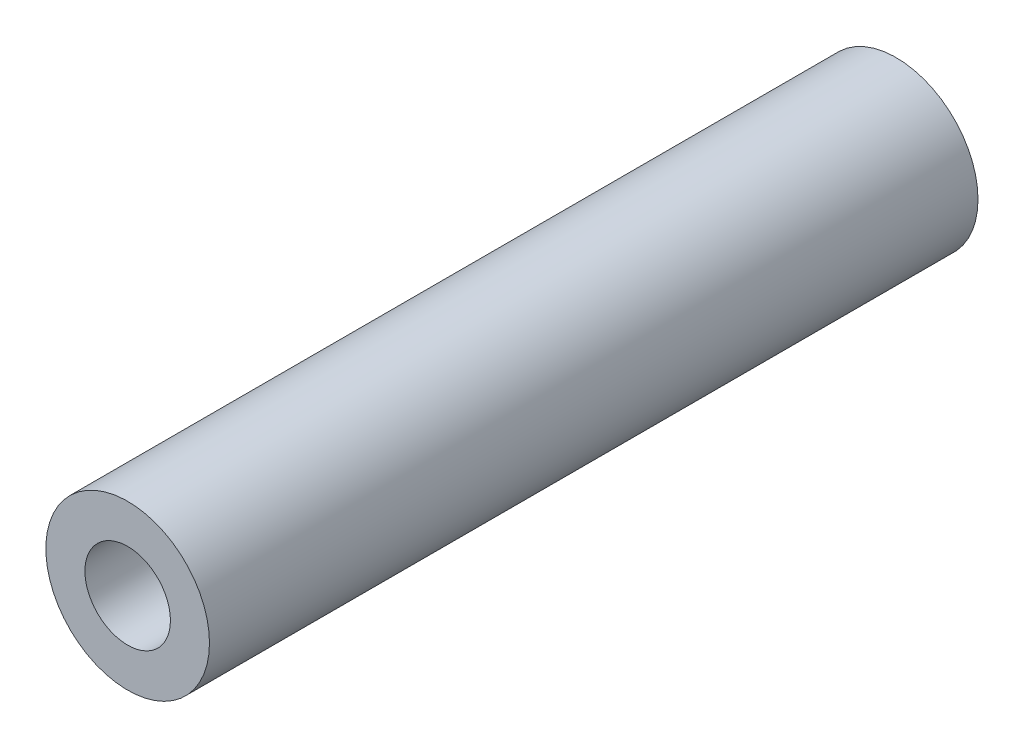
SolidWorks part; units mm, degrees
ref_plane "Front Plane" through (0, 0, 0) normal (0, 0, 1) x (1, 0, 0)
ref_plane "Top Plane" through (0, 0, 0) normal (0, 1, 0) x (1, 0, 0)
ref_plane "Right Plane" through (0, 0, 0) normal (1, 0, 0) x (0, 0, -1)
sketch "Sketch1" plane through (0, 0, 0) normal (0, 0, 1) x (1, 0, 0)
  circle A0 centre (0, 0) radius 2.4892
  circle A1 centre (0, 0) radius 4.7625
  dimension "D1" = 4.9784
  dimension "D2" = 9.525
extrude "Boss-Extrude1" add sketch "Sketch1" along normal mid plane 44.7345
equation "\"D1@Boss-Extrude1\"=1-(1/4)"
